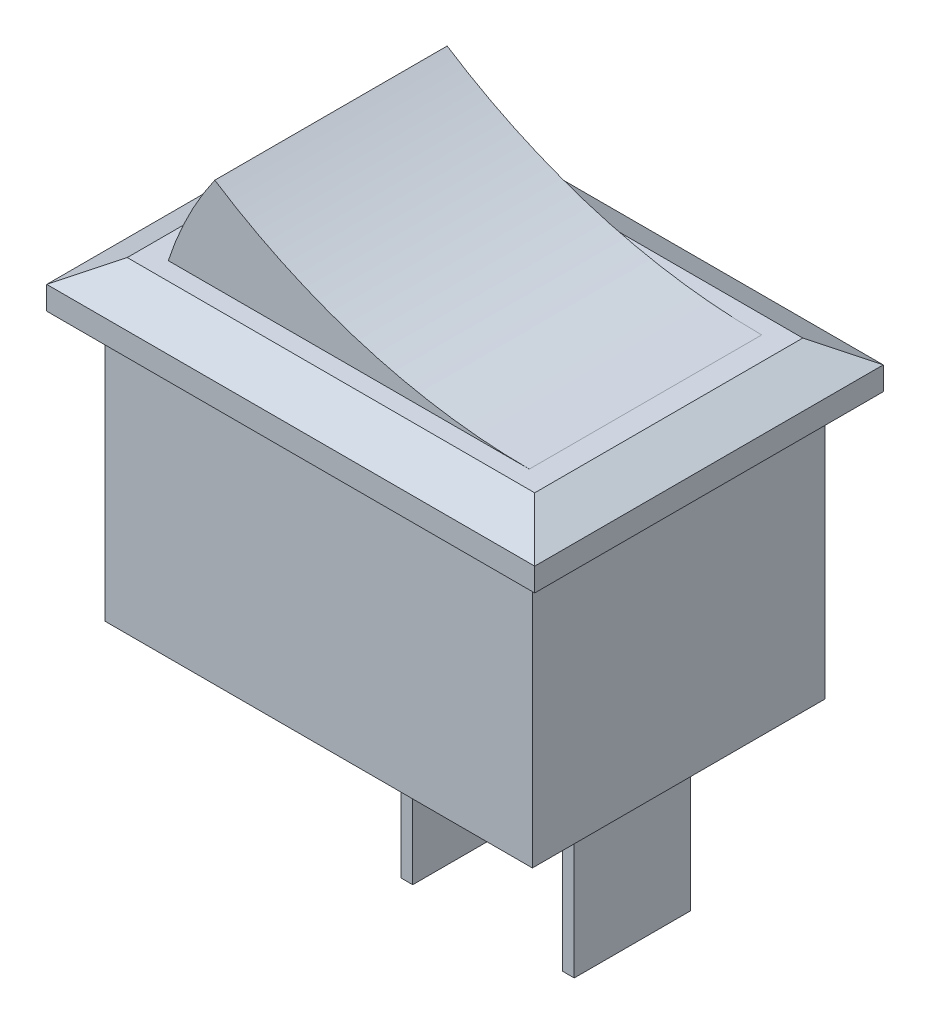
SolidWorks part; units mm, degrees
ref_plane "Front Plane" through (0, 0, 0) normal (0, 0, 1) x (1, 0, 0)
ref_plane "Top Plane" through (0, 0, 0) normal (0, 1, 0) x (1, 0, 0)
ref_plane "Right Plane" through (0, 0, 0) normal (1, 0, 0) x (0, 0, -1)
sketch "Sketch1" plane through (0, 0, 0) normal (0, 1, 0) x (1, 0, 0)
  line L0 (-10.5, 0) -> (10.5, 0) construction
  line L1 (-10.5, -7.5) -> (10.5, -7.5)
  line L2 (-10.5, -7.5) -> (-10.5, 7.5)
  line L3 (-10.5, 7.5) -> (10.5, 7.5)
  line L4 (10.5, -7.5) -> (10.5, 7.5)
  point P8 (0, 0)
  dimension "D1" = 21
  dimension "D2" = 15
extrude "Boss-Extrude1" add sketch "Sketch1" along normal blind 2
chamfer "Chamfer1" distance 1 angle 60 4 edges at (0, 2, -7.5) (10.5, 2, 0) (0, 2, 7.5) (-10.5, 2, 0)
sketch "Sketch2" plane through (0, 0, 0) normal (0, 0, 1) x (1, 0, 0)
  line L0 (-8.7679, 2) -> (8.7679, 2) construction
  line L1 (-7.7679, 2) -> (7.7679, 2)
  arc A0 (7.7679, 2) -> (-5.7679, 6) centre (7.7679, 26.9026) cw
  arc A1 (-7.7679, 2) -> (-5.7679, 6) centre (6.4985, -2.6332) cw
  point P10 (8.7679, 2)
  dimension "D1" = 4
  dimension "D2" = 15
  dimension "D3" = 2
  dimension "D4" = 1
  dimension "D5" = 1
extrude "Boss-Extrude2" add sketch "Sketch2" along normal mid plane 10 separate body
sketch "Sketch3" plane through (0, 0, 0) normal (0, -1, 0) x (1, 0, 0)
  line L0 (-10.5, 0) -> (10.5, 0) construction
  line L1 (-9.2, 6.3) -> (9.2, 6.3)
  line L2 (-9.2, 6.3) -> (-9.2, -6.3)
  line L3 (-9.2, -6.3) -> (9.2, -6.3)
  line L4 (9.2, 6.3) -> (9.2, -6.3)
  line L5 (-10.5, -7.5) -> (-10.5, 7.5) construction
  line L6 (10.5, 7.5) -> (10.5, -7.5) construction
  line L7 (-9.2, 0) -> (9.2, 0) construction
  point P12 (0, 0)
  point P13 (0, 0)
  dimension "D1" = 12.6
  dimension "D2" = 18.4
extrude "Boss-Extrude3" add sketch "Sketch3" along normal blind 11.5
sketch "Sketch4" plane through (0, -11.5, 0) normal (0, -1, 0) x (1, 0, 0)
  line L0 (0.25, 0) -> (-0.25, 0) construction
  line L1 (0.25, -2.5) -> (-0.25, -2.5)
  line L2 (0.25, -2.5) -> (0.25, 2.5)
  line L3 (0.25, 2.5) -> (-0.25, 2.5)
  line L4 (-0.25, -2.5) -> (-0.25, 2.5)
  line L5 (6.7, 2.5) -> (7.2, 2.5)
  line L6 (6.7, 2.5) -> (6.7, -2.5)
  line L7 (6.7, -2.5) -> (7.2, -2.5)
  line L8 (7.2, 2.5) -> (7.2, -2.5)
  line L9 (9.2, -6.3) -> (9.2, 6.3) construction
  point P10 (0, 0)
  dimension "D1" = 2
  dimension "D2" = 0.5
  dimension "D3" = 5
extrude "Boss-Extrude4" add sketch "Sketch4" along normal blind 7 separate body
